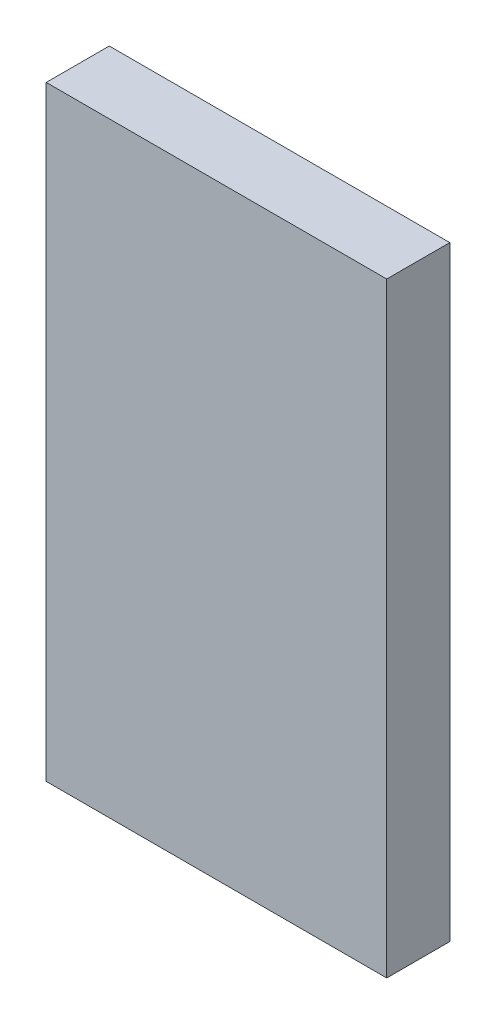
SolidWorks part; units mm, degrees
ref_plane "Front Plane" through (0, 0, 0) normal (0, 0, 1) x (1, 0, 0)
ref_plane "Top Plane" through (0, 0, 0) normal (0, 1, 0) x (1, 0, 0)
ref_plane "Right Plane" through (0, 0, 0) normal (1, 0, 0) x (0, 0, -1)
sketch "Sketch1" plane through (0, 0, 0) normal (0, 0, 1) x (1, 0, 0)
  line L1 (-27, -48) -> (27, -48)
  line L2 (-27, -48) -> (-27, 48)
  line L3 (-27, 48) -> (27, 48)
  line L4 (27, -48) -> (27, 48)
  line L5 (-27, -48) -> (27, 48) construction
  line L6 (-27, 48) -> (27, -48) construction
  point P0 (0, 0)
  dimension "D1" = 54
  dimension "D2" = 96
extrude "Boss-Extrude1" add sketch "Sketch1" along normal blind 10
